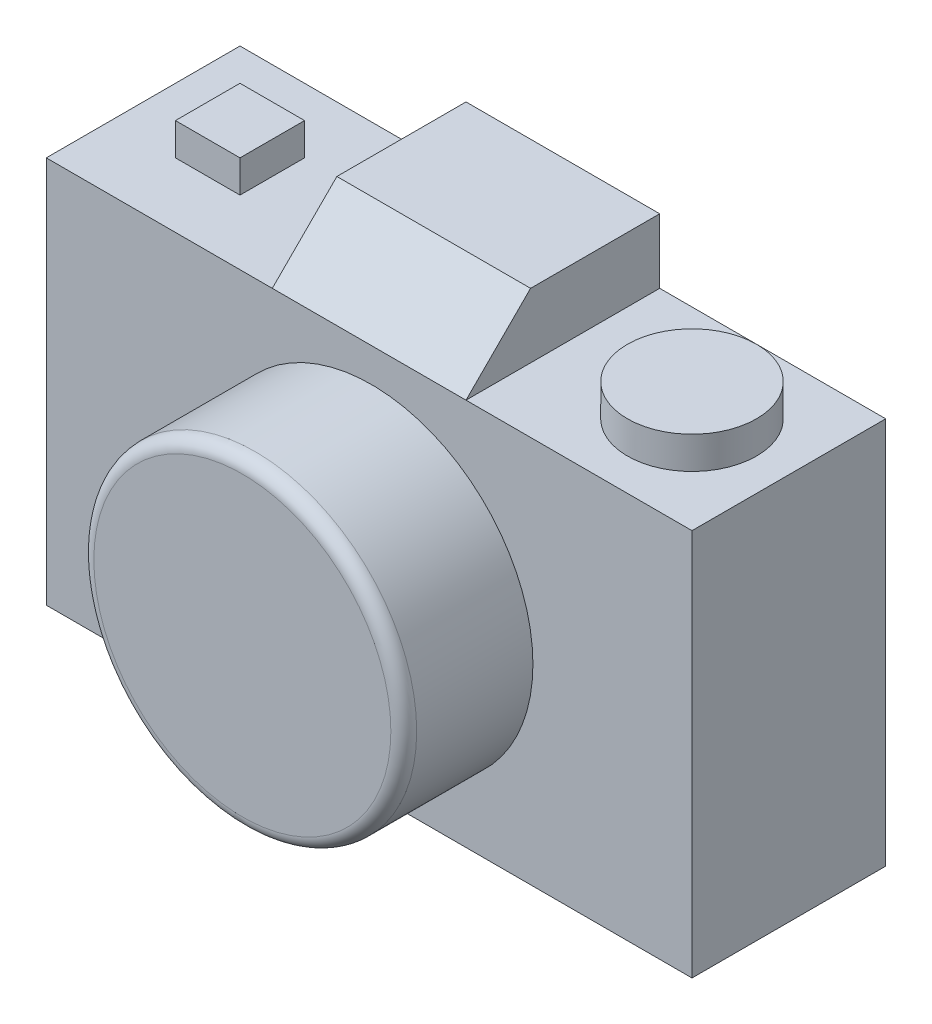
SolidWorks part; units mm, degrees
ref_plane "Front Plane" through (0, 0, 0) normal (0, 0, 1) x (1, 0, 0)
ref_plane "Top Plane" through (0, 0, 0) normal (0, 1, 0) x (1, 0, 0)
ref_plane "Right Plane" through (0, 0, 0) normal (1, 0, 0) x (0, 0, -1)
sketch "Sketch2" plane through (0, 0, 0) normal (0, 0, 1) x (1, 0, 0)
  line L0 (-47.1979, 27.6093) -> (-47.1979, -32.3907)
  line L1 (-47.1979, -32.3907) -> (52.8021, -32.3907)
  line L2 (52.8021, -32.3907) -> (52.8021, 27.6093)
  line L3 (52.8021, 27.6093) -> (-47.1979, 27.6093)
  dimension "D1" = 60
  dimension "D2" = 100
  dimension "D3" = 60
extrude "Boss-Extrude1" add sketch "Sketch2" along normal blind 30 contours L1 L2 L3 L0
sketch "Sketch4" plane through (0, 0, 30) normal (0, 0, 1) x (1, 0, 0)
  line L0 (-47.1979, 27.6093) -> (52.8021, -32.3907)
  circle A0 centre (3.1657, -2.6089) radius 25
extrude "Boss-Extrude2" add sketch "Sketch4" along normal blind 20 contours A0
sketch "Sketch6" plane through (0, 27.6093, 0) normal (0, 1, 0) x (1, 0, 0)
  line L0 (-47.1979, -15) -> (52.8021, -15) construction
  line L1 (-47.1979, -30) -> (-47.1979, 0) construction
  line L2 (52.8021, -30) -> (52.8021, 0) construction
  line L4 (-37.1979, -10) -> (-27.1979, -10)
  line L5 (-37.1979, -10) -> (-37.1979, -20)
  line L6 (-37.1979, -20) -> (-27.1979, -20)
  line L7 (-27.1979, -10) -> (-27.1979, -20)
  line L8 (-37.1979, -10) -> (-27.1979, -20) construction
  line L9 (-37.1979, -20) -> (-27.1979, -10) construction
  circle A0 centre (37.8021, -15) radius 10
  point P6 (-32.1979, -15)
  point P11 (0, 0)
  point P14 (0, 0)
  dimension "D4" = 15
  dimension "D1" = 10
  dimension "D2" = 10
  dimension "D3" = 15
extrude "Boss-Extrude3" add sketch "Sketch6" along normal blind 5
sketch "Sketch8" plane through (0, 27.6093, 0) normal (0, 1, 0) x (1, 0, 0)
  line L0 (-47.1979, -15) -> (52.8021, -15) construction
  line L1 (-47.1979, -30) -> (-47.1979, 0) construction
  line L2 (52.8021, -30) -> (52.8021, 0) construction
  line L3 (-21.8343, -30) -> (28.1657, -30) construction
  line L4 (-12.1979, 0) -> (17.8021, 0)
  line L5 (-12.1979, 0) -> (-12.1979, -30)
  line L6 (-12.1979, -30) -> (17.8021, -30)
  line L7 (17.8021, 0) -> (17.8021, -30)
  line L8 (-12.1979, 0) -> (17.8021, -30) construction
  line L9 (-12.1979, -30) -> (17.8021, 0) construction
  point P6 (2.8021, -15)
  dimension "D1" = 30
  dimension "D2" = 35
extrude "Boss-Extrude4" add sketch "Sketch8" along normal blind 10
chamfer "Chamfer2" distance 10 angle 45 1 edges at (2.8021, 37.6093, 30)
fillet "Fillet1" radius 2 1 edges at (28.1657, -2.6089, 50)
